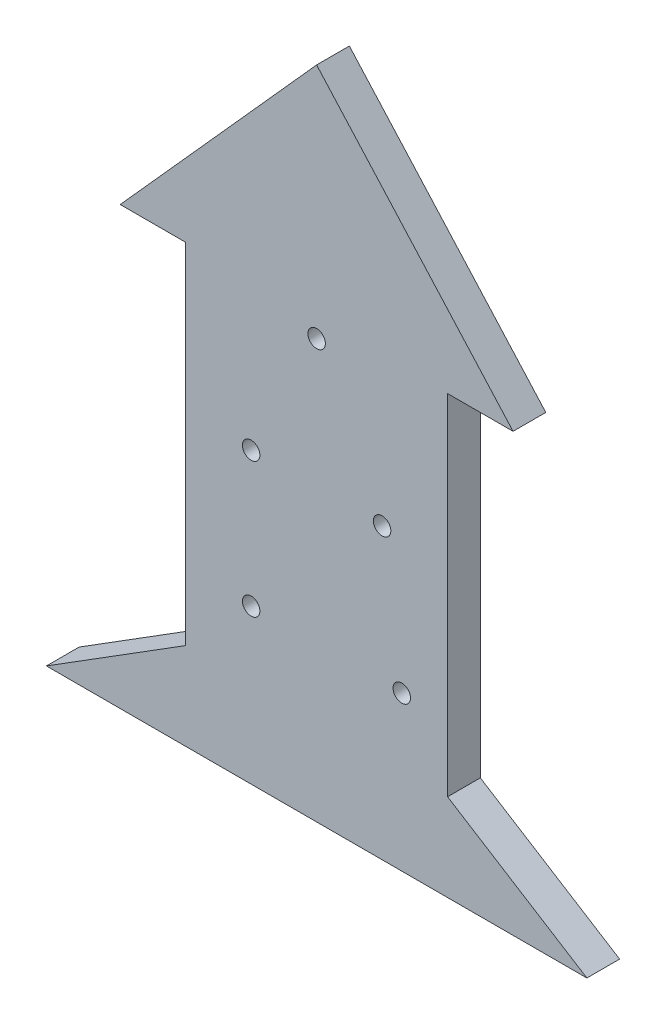
SolidWorks part; units mm, degrees
ref_plane "Plan de face" through (0, 0, 0) normal (0, 0, 1) x (1, 0, 0)
ref_plane "Plan de dessus" through (0, 0, 0) normal (0, 1, 0) x (1, 0, 0)
ref_plane "Plan de droite" through (0, 0, 0) normal (1, 0, 0) x (0, 0, -1)
sketch "Esquisse1" plane through (0, 0, 0) normal (0, 0, 1) x (1, 0, 0)
  line L0 (60, -80.7143) -> (123.821, -120.7143)
  line L1 (0, 179.6861) -> (90, 79.2857)
  line L2 (0, 179.6861) -> (-90, 79.2857)
  line L3 (90, 79.2857) -> (60, 79.2857)
  line L4 (-90, 79.2857) -> (-60, 79.2857)
  line L5 (-60, 79.2857) -> (-60, -80.7143)
  line L9 (60, -80.7143) -> (60, 79.2857)
  line L10 (-60, -80.7143) -> (-123.82, -120.7143)
  line L11 (123.821, -120.7143) -> (-123.82, -120.7143)
  circle A0 centre (30, -47.8669) radius 4
  circle A1 centre (30, -23.7058) radius 4
  circle A2 centre (-30, -47.8669) radius 4
  circle A3 centre (-30, -23.7058) radius 4
  circle A4 centre (0, 64.6517) radius 4
  dimension "D15" = 30
  dimension "D19" = 8
  dimension "D20" = 8
  dimension "D21" = 8
  dimension "D22" = 8
  dimension "D27" = 8
  dimension "D29" = 60
  dimension "D1" = 60
  dimension "D2" = 60
  dimension "D3" = 30
  dimension "D4" = 30
  dimension "D5" = 179.6861
  dimension "D6" = 79.2857
  dimension "D7" = 79.2857
  dimension "D8" = 119.9381
  dimension "D9" = 160
  dimension "D10" = 160
  dimension "D11" = 40
  dimension "D12" = 40
  dimension "D13" = 123.821
  dimension "D14" = 123.82
  dimension "D16" = 30
  dimension "D17" = 30
  dimension "D18" = 30
  dimension "D23" = 38.2357
  dimension "D24" = 38.2357
  dimension "D25" = 56.4911
  dimension "D26" = 56.4911
  dimension "D28" = 64.6517
extrude "Boss.-Extru.1" add sketch "Esquisse1" along normal blind 15 contours L5 L10 L11 L0 L9 L3 L1 L2 L4
sketch "Esquisse2" plane through (0, 0, 15) normal (0, 0, 1) x (1, 0, 0)
  line L0 (60, -80.7143) -> (60, 79.2857) construction
  line L1 (-60, 79.2857) -> (-60, -80.7143) construction
  circle A0 centre (30, -41.2252) radius 4
  circle A1 centre (30, 8.7748) radius 4
  circle A2 centre (-30, 8.7748) radius 4
  circle A3 centre (-30, -41.2252) radius 4
  circle A5 centre (0, 71.0926) radius 4
  dimension "D1" = 30
  dimension "D3" = 8
  dimension "D4" = 8
  dimension "D5" = 50
  dimension "D6" = 8
  dimension "D7" = 8
  dimension "D13" = 8
  dimension "D2" = 30
  dimension "D8" = 30
  dimension "D9" = 30
  dimension "D10" = 31.257
  dimension "D11" = 31.257
  dimension "D12" = 50.9854
  dimension "D14" = 71.0926
extrude "Enlèv. mat.-Extru.2" cut sketch "Esquisse2" against normal blind 60 contours A5
sketch "Esquisse4" plane through (0, 0, 15) normal (0, 0, 1) x (1, 0, 0)
  line L0 (60, -80.7143) -> (60, 79.2857) construction
  line L2 (-60, 79.2857) -> (-60, -80.7143) construction
  circle A0 centre (30, 11.7869) radius 4
  circle A1 centre (39.0138, -50.0537) radius 4
  circle A2 centre (-30, 11.7869) radius 4
  circle A3 centre (-30, -50.0537) radius 4
  point P10 (0, 0)
  dimension "D1" = 8
  dimension "D2" = 8
  dimension "D3" = 8
  dimension "D4" = 8
  dimension "D5" = 30
  dimension "D6" = 30
  dimension "D7" = 32.2325
  dimension "D8" = 32.2325
  dimension "D9" = 30
  dimension "D10" = 50.0537
  dimension "D11" = 58.3556
extrude "Enlèv. mat.-Extru.3" cut sketch "Esquisse4" against normal blind 60
